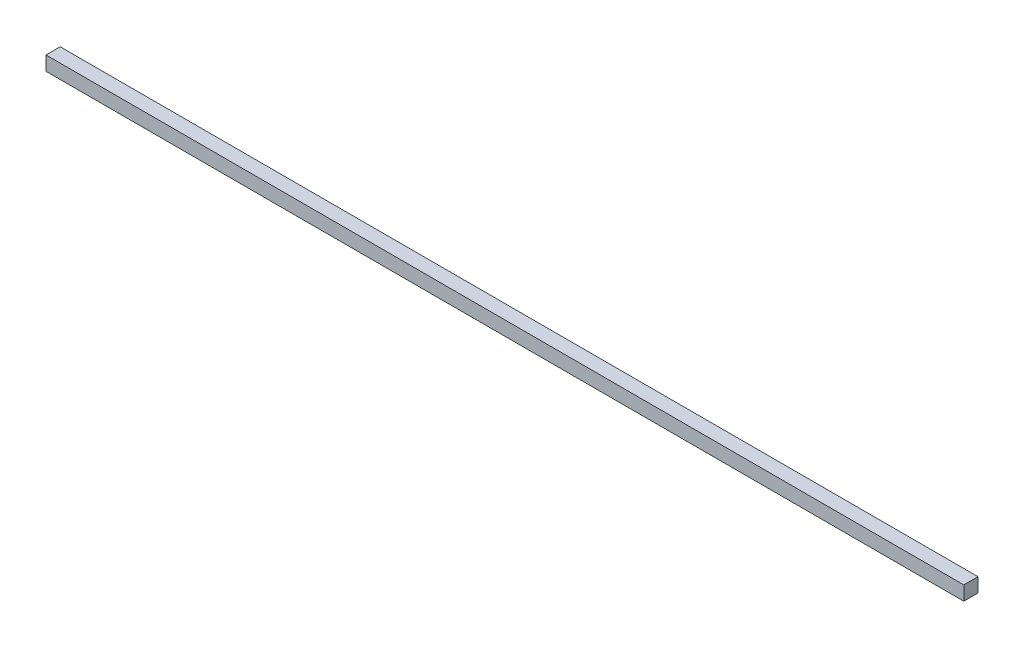
SolidWorks part; units mm, degrees
material "Pine"
ref_plane "Piano frontale" through (0, 0, 0) normal (0, 0, 1) x (1, 0, 0)
ref_plane "Piano superiore" through (0, 0, 0) normal (0, 1, 0) x (1, 0, 0)
ref_plane "Piano destro" through (0, 0, 0) normal (1, 0, 0) x (0, 0, -1)
sketch "Sketch1" plane through (0, 0, 0) normal (0, 0, 1) x (1, 0, 0)
  line L1 (0, 0) -> (97, 0)
  line L2 (0, 0) -> (0, 1.5)
  line L3 (0, 1.5) -> (97, 1.5)
  line L4 (97, 0) -> (97, 1.5)
  dimension "D1" = 97
  dimension "D2" = 1.5
extrude "Boss-Extrude1" add sketch "Sketch1" along normal blind 1.5
scale "Scale1" scale about origin uniform scaling yes scale factor 10
